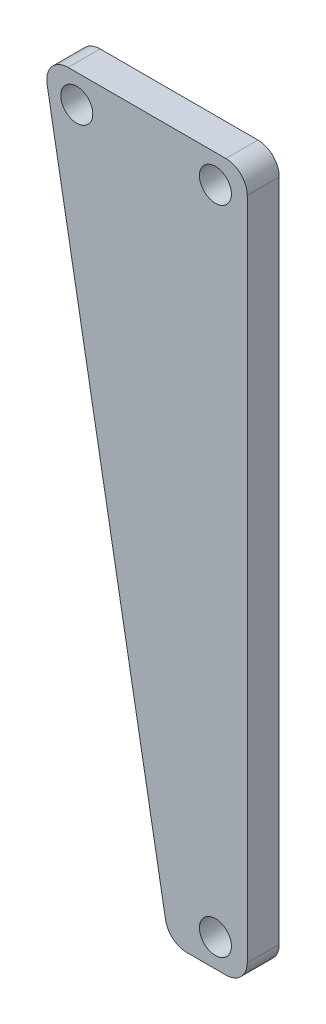
SolidWorks part; units mm, degrees
ref_plane "Front Plane" through (0, 0, 0) normal (0, 0, 1) x (1, 0, 0)
ref_plane "Top Plane" through (0, 0, 0) normal (0, 1, 0) x (1, 0, 0)
ref_plane "Right Plane" through (0, 0, 0) normal (1, 0, 0) x (0, 0, -1)
sketch "Sketch1" plane through (0, 0, 0) normal (0, 0, 1) x (1, 0, 0)
  line L0 (-194.9058, 150.9444) -> (-46.8857, 150.9444)
  line L1 (-26.8857, 130.9444) -> (-26.8857, -492.1197)
  line L2 (-46.8857, -512.1197) -> (-83.7604, -512.1197)
  line L3 (-103.4496, -495.6319) -> (-214.595, 127.4321)
  circle A0 centre (-186.7273, 124.6818) radius 15
  circle A1 centre (-56.7273, 124.6818) radius 15
  circle A2 centre (-56.7273, -486.1182) radius 15
  arc A3 (-83.7604, -512.1197) -> (-103.4496, -495.6319) centre (-83.7604, -492.1197) cw
  arc A4 (-26.8857, -492.1197) -> (-46.8857, -512.1197) centre (-46.8857, -492.1197) cw
  arc A5 (-26.8857, 130.9444) -> (-46.8857, 150.9444) centre (-46.8857, 130.9444) ccw
  arc A6 (-194.9058, 150.9444) -> (-214.595, 127.4321) centre (-194.9058, 130.9444) ccw
  point P18 (-26.8857, 130.9444)
  point P19 (-214.9058, 130.9444)
  point P20 (-83.7604, -512.1197)
  dimension "D3" = 30
  dimension "D4" = 30
  dimension "D5" = 30
  dimension "D6" = 20
  dimension "D1" = 130
  dimension "D2" = 610.8
extrude "Boss-Extrude1" add sketch "Sketch1" along normal blind 30
